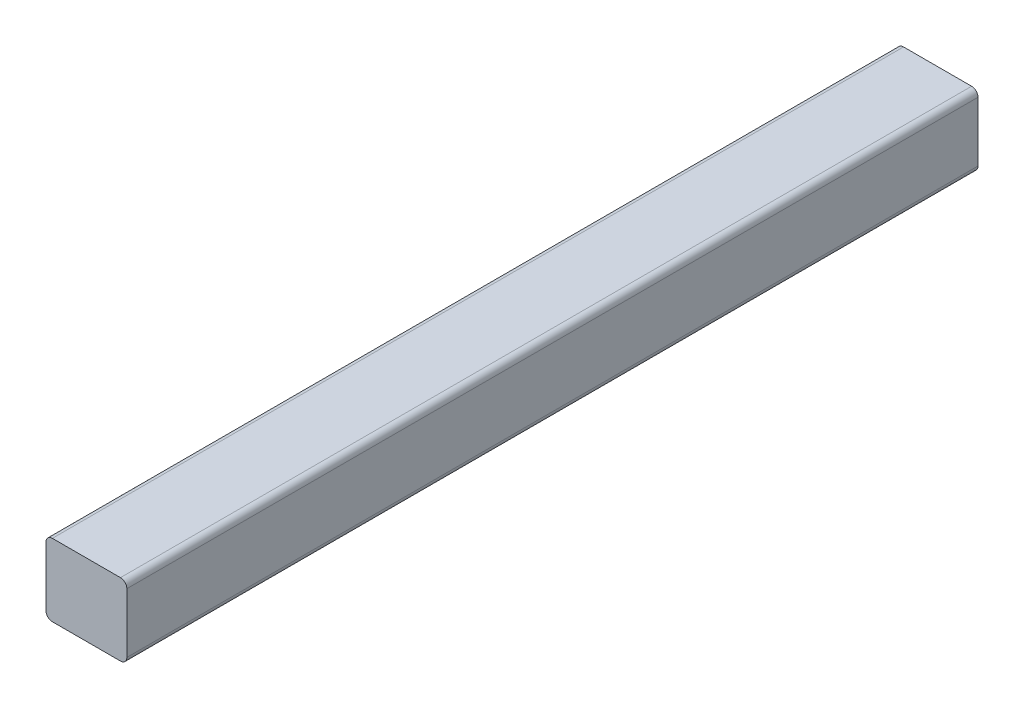
SolidWorks part; units mm, degrees
ref_plane "Ön Düzlem" through (0, 0, 0) normal (0, 0, 1) x (1, 0, 0)
ref_plane "Üst Düzlem" through (0, 0, 0) normal (0, 1, 0) x (1, 0, 0)
ref_plane "Sağ Düzlem" through (0, 0, 0) normal (1, 0, 0) x (0, 0, -1)
sketch "Model" plane through (0, 0, 0) normal (0, 0, 1) x (1, 0, 0)
  line L0 (-9.5, 79.7049) -> (9.5, 79.7049)
  line L1 (60.5945, 121.4987) -> (60.8885, 121.3363)
  line L2 (60.8885, 121.3363) -> (61.139, 121.1124)
  line L3 (61.139, 121.1124) -> (61.3334, 120.8385)
  line L4 (61.3334, 120.8385) -> (61.4619, 120.5282)
  line L5 (61.4619, 120.5282) -> (61.5182, 120.197)
  line L6 (61.5182, 120.197) -> (61.4993, 119.8617)
  line L7 (61.4993, 119.8617) -> (61.4063, 119.5389)
  line L8 (61.4063, 119.5389) -> (45.7726, 92.4605)
  line L9 (45.7726, 92.4605) -> (42.0525, 92.3778)
  line L10 (42.0525, 92.3778) -> (41.4785, 90.992)
  line L11 (58.0621, 81.4174) -> (58.9753, 82.6074)
  line L12 (58.9753, 82.6074) -> (57.1868, 85.8705)
  line L13 (57.1868, 85.8705) -> (72.8206, 112.9489)
  line L14 (72.8206, 112.9489) -> (73.0536, 113.1908)
  line L15 (73.0536, 113.1908) -> (73.3346, 113.3748)
  line L16 (73.3346, 113.3748) -> (73.6495, 113.4917)
  line L17 (73.6495, 113.4917) -> (73.9825, 113.5355)
  line L18 (73.9825, 113.5355) -> (74.317, 113.5041)
  line L19 (74.317, 113.5041) -> (74.636, 113.3991)
  line L20 (74.636, 113.3991) -> (74.9237, 113.2258)
  line L21 (74.9237, 113.2258) -> (89.976, 101.6758)
  line L22 (89.976, 101.6758) -> (90.2179, 101.4427)
  line L23 (90.2179, 101.4427) -> (90.4019, 101.1617)
  line L24 (90.4019, 101.1617) -> (90.5188, 100.8468)
  line L25 (90.5188, 100.8468) -> (90.5626, 100.5138)
  line L26 (90.5626, 100.5138) -> (90.5313, 100.1793)
  line L27 (90.5313, 100.1793) -> (90.4263, 99.8603)
  line L28 (90.4263, 99.8603) -> (90.2529, 99.5726)
  line L29 (90.2529, 99.5726) -> (68.1435, 77.4631)
  line L30 (68.1435, 77.4631) -> (64.5287, 78.3461)
  line L31 (64.5287, 78.3461) -> (63.6156, 77.1561)
  line L32 (77.1561, 63.6156) -> (78.3461, 64.5287)
  line L33 (78.3461, 64.5287) -> (77.4631, 68.1435)
  line L34 (77.4631, 68.1435) -> (99.5726, 90.2529)
  line L35 (99.5726, 90.2529) -> (99.8603, 90.4263)
  line L36 (99.8603, 90.4263) -> (100.1793, 90.5313)
  line L37 (100.1793, 90.5313) -> (100.5138, 90.5626)
  line L38 (100.5138, 90.5626) -> (100.8468, 90.5188)
  line L39 (100.8468, 90.5188) -> (101.1617, 90.4019)
  line L40 (101.1617, 90.4019) -> (101.4427, 90.2179)
  line L41 (101.4427, 90.2179) -> (101.6758, 89.976)
  line L42 (101.6758, 89.976) -> (113.2258, 74.9237)
  line L43 (113.2258, 74.9237) -> (113.3991, 74.636)
  line L44 (113.3991, 74.636) -> (113.5041, 74.317)
  line L45 (113.5041, 74.317) -> (113.5355, 73.9825)
  line L46 (113.5355, 73.9825) -> (113.4917, 73.6495)
  line L47 (113.4917, 73.6495) -> (113.3748, 73.3346)
  line L48 (113.3748, 73.3346) -> (113.1908, 73.0536)
  line L49 (113.1908, 73.0536) -> (112.9489, 72.8206)
  line L50 (112.9489, 72.8206) -> (85.8705, 57.1868)
  line L51 (85.8705, 57.1868) -> (82.6074, 58.9753)
  line L52 (82.6074, 58.9753) -> (81.4174, 58.0621)
  line L53 (90.992, 41.4785) -> (92.3778, 42.0525)
  line L54 (92.3778, 42.0525) -> (92.4605, 45.7726)
  line L55 (92.4605, 45.7726) -> (119.5389, 61.4063)
  line L56 (119.5389, 61.4063) -> (119.8617, 61.4993)
  line L57 (119.8617, 61.4993) -> (120.197, 61.5182)
  line L58 (120.197, 61.5182) -> (120.5282, 61.4619)
  line L59 (120.5282, 61.4619) -> (120.8385, 61.3334)
  line L60 (120.8385, 61.3334) -> (121.1124, 61.139)
  line L61 (121.1124, 61.139) -> (121.3363, 60.8885)
  line L62 (121.3363, 60.8885) -> (121.4987, 60.5945)
  line L63 (121.4987, 60.5945) -> (128.7594, 43.0658)
  line L64 (128.7594, 43.0658) -> (128.8524, 42.743)
  line L65 (128.8524, 42.743) -> (128.8712, 42.4076)
  line L66 (128.8712, 42.4076) -> (128.815, 42.0765)
  line L67 (128.815, 42.0765) -> (128.6864, 41.7662)
  line L68 (128.6864, 41.7662) -> (128.492, 41.4922)
  line L69 (128.492, 41.4922) -> (128.2416, 41.2684)
  line L70 (128.2416, 41.2684) -> (127.9476, 41.1059)
  line L71 (127.9476, 41.1059) -> (97.7455, 33.0133)
  line L72 (97.7455, 33.0133) -> (95.0566, 35.5853)
  line L73 (95.0566, 35.5853) -> (93.6707, 35.0113)
  line L74 (98.6269, 16.5147) -> (100.1141, 16.7105)
  line L75 (100.1141, 16.7105) -> (101.1568, 20.2824)
  line L76 (101.1568, 20.2824) -> (131.3588, 28.375)
  line L77 (131.3588, 28.375) -> (131.6947, 28.3813)
  line L78 (131.6947, 28.3813) -> (132.0235, 28.3127)
  line L79 (132.0235, 28.3127) -> (132.3288, 28.1726)
  line L80 (132.3288, 28.1726) -> (132.5953, 27.9682)
  line L81 (132.5953, 27.9682) -> (132.8096, 27.7095)
  line L82 (132.8096, 27.7095) -> (132.9609, 27.4097)
  line L83 (132.9609, 27.4097) -> (133.0418, 27.0836)
  line L84 (133.0418, 27.0836) -> (135.5183, 8.273)
  line L85 (135.5183, 8.273) -> (135.5246, 7.9371)
  line L86 (135.5246, 7.9371) -> (135.4559, 7.6083)
  line L87 (135.4559, 7.6083) -> (135.3159, 7.303)
  line L88 (135.3159, 7.303) -> (135.1114, 7.0365)
  line L89 (135.1114, 7.0365) -> (134.8528, 6.8222)
  line L90 (134.8528, 6.8222) -> (134.5529, 6.6709)
  line L91 (134.5529, 6.6709) -> (134.2269, 6.59)
  line L92 (134.2269, 6.59) -> (102.9594, 6.59)
  line L93 (102.9594, 6.59) -> (101.0278, 9.7704)
  line L94 (101.0278, 9.7704) -> (99.5406, 9.5746)
  line L95 (99.5406, -9.5746) -> (101.0278, -9.7704)
  line L96 (101.0278, -9.7704) -> (102.9594, -6.59)
  line L97 (102.9594, -6.59) -> (134.2269, -6.59)
  line L98 (134.2269, -6.59) -> (134.5529, -6.6709)
  line L99 (134.5529, -6.6709) -> (134.8528, -6.8222)
  line L100 (134.8528, -6.8222) -> (135.1114, -7.0365)
  line L101 (135.1114, -7.0365) -> (135.3159, -7.303)
  line L102 (135.3159, -7.303) -> (135.4559, -7.6083)
  line L103 (135.4559, -7.6083) -> (135.5246, -7.9371)
  line L104 (135.5246, -7.9371) -> (135.5183, -8.273)
  line L105 (135.5183, -8.273) -> (133.0418, -27.0836)
  line L106 (133.0418, -27.0836) -> (132.9609, -27.4097)
  line L107 (132.9609, -27.4097) -> (132.8096, -27.7095)
  line L108 (132.8096, -27.7095) -> (132.5953, -27.9682)
  line L109 (132.5953, -27.9682) -> (132.3288, -28.1726)
  line L110 (132.3288, -28.1726) -> (132.0235, -28.3127)
  line L111 (132.0235, -28.3127) -> (131.6947, -28.3813)
  line L112 (131.6947, -28.3813) -> (131.3588, -28.375)
  line L113 (131.3588, -28.375) -> (101.1568, -20.2824)
  line L114 (101.1568, -20.2824) -> (100.1141, -16.7105)
  line L115 (100.1141, -16.7105) -> (98.6269, -16.5147)
  line L116 (93.6707, -35.0113) -> (95.0566, -35.5853)
  line L117 (95.0566, -35.5853) -> (97.7455, -33.0133)
  line L118 (97.7455, -33.0133) -> (127.9476, -41.1059)
  line L119 (127.9476, -41.1059) -> (128.2416, -41.2684)
  line L120 (128.2416, -41.2684) -> (128.492, -41.4922)
  line L121 (128.492, -41.4922) -> (128.6864, -41.7662)
  line L122 (128.6864, -41.7662) -> (128.815, -42.0765)
  line L123 (128.815, -42.0765) -> (128.8712, -42.4076)
  line L124 (128.8712, -42.4076) -> (128.8524, -42.743)
  line L125 (128.8524, -42.743) -> (128.7594, -43.0658)
  line L126 (128.7594, -43.0658) -> (121.4987, -60.5945)
  line L127 (121.4987, -60.5945) -> (121.3363, -60.8885)
  line L128 (121.3363, -60.8885) -> (121.1124, -61.139)
  line L129 (121.1124, -61.139) -> (120.8385, -61.3334)
  line L130 (120.8385, -61.3334) -> (120.5282, -61.4619)
  line L131 (120.5282, -61.4619) -> (120.197, -61.5182)
  line L132 (120.197, -61.5182) -> (119.8617, -61.4993)
  line L133 (119.8617, -61.4993) -> (119.5389, -61.4063)
  line L134 (119.5389, -61.4063) -> (92.4605, -45.7726)
  line L135 (92.4605, -45.7726) -> (92.3778, -42.0525)
  line L136 (92.3778, -42.0525) -> (90.992, -41.4785)
  line L137 (81.4174, -58.0621) -> (82.6074, -58.9753)
  line L138 (82.6074, -58.9753) -> (85.8705, -57.1868)
  line L139 (85.8705, -57.1868) -> (112.9489, -72.8206)
  line L140 (112.9489, -72.8206) -> (113.1908, -73.0536)
  line L141 (113.1908, -73.0536) -> (113.3748, -73.3346)
  line L142 (113.3748, -73.3346) -> (113.4917, -73.6495)
  line L143 (113.4917, -73.6495) -> (113.5355, -73.9825)
  line L144 (113.5355, -73.9825) -> (113.5041, -74.317)
  line L145 (113.5041, -74.317) -> (113.3991, -74.636)
  line L146 (113.3991, -74.636) -> (113.2258, -74.9237)
  line L147 (113.2258, -74.9237) -> (101.6758, -89.976)
  line L148 (101.6758, -89.976) -> (101.4427, -90.2179)
  line L149 (101.4427, -90.2179) -> (101.1617, -90.4019)
  line L150 (101.1617, -90.4019) -> (100.8468, -90.5188)
  line L151 (100.8468, -90.5188) -> (100.5138, -90.5626)
  line L152 (100.5138, -90.5626) -> (100.1793, -90.5313)
  line L153 (100.1793, -90.5313) -> (99.8603, -90.4263)
  line L154 (99.8603, -90.4263) -> (99.5726, -90.2529)
  line L155 (99.5726, -90.2529) -> (77.4631, -68.1435)
  line L156 (77.4631, -68.1435) -> (78.3461, -64.5287)
  line L157 (78.3461, -64.5287) -> (77.1561, -63.6156)
  line L158 (63.6156, -77.1561) -> (64.5287, -78.3461)
  line L159 (64.5287, -78.3461) -> (68.1435, -77.4631)
  line L160 (68.1435, -77.4631) -> (90.2529, -99.5726)
  line L161 (90.2529, -99.5726) -> (90.4263, -99.8603)
  line L162 (90.4263, -99.8603) -> (90.5313, -100.1793)
  line L163 (90.5313, -100.1793) -> (90.5626, -100.5138)
  line L164 (90.5626, -100.5138) -> (90.5188, -100.8468)
  line L165 (90.5188, -100.8468) -> (90.4019, -101.1617)
  line L166 (90.4019, -101.1617) -> (90.2179, -101.4427)
  line L167 (90.2179, -101.4427) -> (89.976, -101.6758)
  line L168 (89.976, -101.6758) -> (74.9237, -113.2258)
  line L169 (74.9237, -113.2258) -> (74.636, -113.3991)
  line L170 (74.636, -113.3991) -> (74.317, -113.5041)
  line L171 (74.317, -113.5041) -> (73.9825, -113.5355)
  line L172 (73.9825, -113.5355) -> (73.6495, -113.4917)
  line L173 (73.6495, -113.4917) -> (73.3346, -113.3748)
  line L174 (73.3346, -113.3748) -> (73.0536, -113.1908)
  line L175 (73.0536, -113.1908) -> (72.8206, -112.9489)
  line L176 (72.8206, -112.9489) -> (57.1868, -85.8705)
  line L177 (57.1868, -85.8705) -> (58.9753, -82.6074)
  line L178 (58.9753, -82.6074) -> (58.0621, -81.4174)
  line L179 (41.4785, -90.992) -> (42.0525, -92.3778)
  line L180 (42.0525, -92.3778) -> (45.7726, -92.4605)
  line L181 (45.7726, -92.4605) -> (61.4063, -119.5389)
  line L182 (61.4063, -119.5389) -> (61.4993, -119.8617)
  line L183 (61.4993, -119.8617) -> (61.5182, -120.197)
  line L184 (61.5182, -120.197) -> (61.4619, -120.5282)
  line L185 (61.4619, -120.5282) -> (61.3334, -120.8385)
  line L186 (61.3334, -120.8385) -> (61.139, -121.1124)
  line L187 (61.139, -121.1124) -> (60.8885, -121.3363)
  line L188 (60.8885, -121.3363) -> (60.5945, -121.4987)
  line L189 (60.5945, -121.4987) -> (43.0658, -128.7594)
  line L190 (43.0658, -128.7594) -> (42.743, -128.8524)
  line L191 (42.743, -128.8524) -> (42.4076, -128.8712)
  line L192 (42.4076, -128.8712) -> (42.0765, -128.815)
  line L193 (42.0765, -128.815) -> (41.7662, -128.6864)
  line L194 (41.7662, -128.6864) -> (41.4922, -128.492)
  line L195 (41.4922, -128.492) -> (41.2684, -128.2416)
  line L196 (41.2684, -128.2416) -> (41.1059, -127.9476)
  line L197 (41.1059, -127.9476) -> (33.0133, -97.7455)
  line L198 (33.0133, -97.7455) -> (35.5853, -95.0566)
  line L199 (35.5853, -95.0566) -> (35.0113, -93.6707)
  line L200 (16.5147, -98.6269) -> (16.7105, -100.1141)
  line L201 (16.7105, -100.1141) -> (20.2824, -101.1568)
  line L202 (20.2824, -101.1568) -> (28.375, -131.3588)
  line L203 (28.375, -131.3588) -> (28.3813, -131.6947)
  line L204 (28.3813, -131.6947) -> (28.3127, -132.0235)
  line L205 (28.3127, -132.0235) -> (28.1726, -132.3288)
  line L206 (28.1726, -132.3288) -> (27.9682, -132.5953)
  line L207 (27.9682, -132.5953) -> (27.7095, -132.8096)
  line L208 (27.7095, -132.8096) -> (27.4097, -132.9609)
  line L209 (27.4097, -132.9609) -> (27.0836, -133.0418)
  line L210 (27.0836, -133.0418) -> (8.273, -135.5183)
  line L211 (8.273, -135.5183) -> (7.9371, -135.5246)
  line L212 (7.9371, -135.5246) -> (7.6083, -135.4559)
  line L213 (7.6083, -135.4559) -> (7.303, -135.3159)
  line L214 (7.303, -135.3159) -> (7.0365, -135.1114)
  line L215 (7.0365, -135.1114) -> (6.8222, -134.8528)
  line L216 (6.8222, -134.8528) -> (6.6709, -134.5529)
  line L217 (6.6709, -134.5529) -> (6.59, -134.2269)
  line L218 (6.59, -134.2269) -> (6.59, -102.9594)
  line L219 (6.59, -102.9594) -> (9.7704, -101.0278)
  line L220 (9.7704, -101.0278) -> (9.5746, -99.5406)
  line L221 (-9.5746, -99.5406) -> (-9.7704, -101.0278)
  line L222 (-9.7704, -101.0278) -> (-6.59, -102.9594)
  line L223 (-6.59, -102.9594) -> (-6.59, -134.2269)
  line L224 (-6.59, -134.2269) -> (-6.6709, -134.5529)
  line L225 (-6.6709, -134.5529) -> (-6.8222, -134.8528)
  line L226 (-6.8222, -134.8528) -> (-7.0365, -135.1114)
  line L227 (-7.0365, -135.1114) -> (-7.303, -135.3159)
  line L228 (-7.303, -135.3159) -> (-7.6083, -135.4559)
  line L229 (-7.6083, -135.4559) -> (-7.9371, -135.5246)
  line L230 (-7.9371, -135.5246) -> (-8.273, -135.5183)
  line L231 (-8.273, -135.5183) -> (-27.0836, -133.0418)
  line L232 (-27.0836, -133.0418) -> (-27.4097, -132.9609)
  line L233 (-27.4097, -132.9609) -> (-27.7095, -132.8096)
  line L234 (-27.7095, -132.8096) -> (-27.9682, -132.5953)
  line L235 (-27.9682, -132.5953) -> (-28.1726, -132.3288)
  line L236 (-28.1726, -132.3288) -> (-28.3127, -132.0235)
  line L237 (-28.3127, -132.0235) -> (-28.3813, -131.6947)
  line L238 (-28.3813, -131.6947) -> (-28.375, -131.3588)
  line L239 (-28.375, -131.3588) -> (-20.2824, -101.1568)
  line L240 (-20.2824, -101.1568) -> (-16.7105, -100.1141)
  line L241 (-16.7105, -100.1141) -> (-16.5147, -98.6269)
  line L242 (-35.0113, -93.6707) -> (-35.5853, -95.0566)
  line L243 (-35.5853, -95.0566) -> (-33.0133, -97.7455)
  line L244 (-33.0133, -97.7455) -> (-41.1059, -127.9476)
  line L245 (-41.1059, -127.9476) -> (-41.2684, -128.2416)
  line L246 (-41.2684, -128.2416) -> (-41.4922, -128.492)
  line L247 (-41.4922, -128.492) -> (-41.7662, -128.6864)
  line L248 (-41.7662, -128.6864) -> (-42.0765, -128.815)
  line L249 (-42.0765, -128.815) -> (-42.4076, -128.8712)
  line L250 (-42.4076, -128.8712) -> (-42.743, -128.8524)
  line L251 (-42.743, -128.8524) -> (-43.0658, -128.7594)
  line L252 (-43.0658, -128.7594) -> (-60.5945, -121.4987)
  line L253 (-60.5945, -121.4987) -> (-60.8885, -121.3363)
  line L254 (-60.8885, -121.3363) -> (-61.139, -121.1124)
  line L255 (-61.139, -121.1124) -> (-61.3334, -120.8385)
  line L256 (-61.3334, -120.8385) -> (-61.4619, -120.5282)
  line L257 (-61.4619, -120.5282) -> (-61.5182, -120.197)
  line L258 (-61.5182, -120.197) -> (-61.4993, -119.8617)
  line L259 (-61.4993, -119.8617) -> (-61.4063, -119.5389)
  line L260 (-61.4063, -119.5389) -> (-45.7726, -92.4605)
  line L261 (-45.7726, -92.4605) -> (-42.0525, -92.3778)
  line L262 (-42.0525, -92.3778) -> (-41.4785, -90.992)
  line L263 (-58.0621, -81.4174) -> (-58.9753, -82.6074)
  line L264 (-58.9753, -82.6074) -> (-57.1868, -85.8705)
  line L265 (-57.1868, -85.8705) -> (-72.8206, -112.9489)
  line L266 (-72.8206, -112.9489) -> (-73.0536, -113.1908)
  line L267 (-73.0536, -113.1908) -> (-73.3346, -113.3748)
  line L268 (-73.3346, -113.3748) -> (-73.6495, -113.4917)
  line L269 (-73.6495, -113.4917) -> (-73.9825, -113.5355)
  line L270 (-73.9825, -113.5355) -> (-74.317, -113.5041)
  line L271 (-74.317, -113.5041) -> (-74.636, -113.3991)
  line L272 (-74.636, -113.3991) -> (-74.9237, -113.2258)
  line L273 (-74.9237, -113.2258) -> (-89.976, -101.6758)
  line L274 (-89.976, -101.6758) -> (-90.2179, -101.4427)
  line L275 (-90.2179, -101.4427) -> (-90.4019, -101.1617)
  line L276 (-90.4019, -101.1617) -> (-90.5188, -100.8468)
  line L277 (-90.5188, -100.8468) -> (-90.5626, -100.5138)
  line L278 (-90.5626, -100.5138) -> (-90.5313, -100.1793)
  line L279 (-90.5313, -100.1793) -> (-90.4263, -99.8603)
  line L280 (-90.4263, -99.8603) -> (-90.2529, -99.5726)
  line L281 (-90.2529, -99.5726) -> (-68.1435, -77.4631)
  line L282 (-68.1435, -77.4631) -> (-64.5287, -78.3461)
  line L283 (-64.5287, -78.3461) -> (-63.6156, -77.1561)
  line L284 (-77.1561, -63.6156) -> (-78.3461, -64.5287)
  line L285 (-78.3461, -64.5287) -> (-77.4631, -68.1435)
  line L286 (-77.4631, -68.1435) -> (-99.5726, -90.2529)
  line L287 (-99.5726, -90.2529) -> (-99.8603, -90.4263)
  line L288 (-99.8603, -90.4263) -> (-100.1793, -90.5313)
  line L289 (-100.1793, -90.5313) -> (-100.5138, -90.5626)
  line L290 (-100.5138, -90.5626) -> (-100.8468, -90.5188)
  line L291 (-100.8468, -90.5188) -> (-101.1617, -90.4019)
  line L292 (-101.1617, -90.4019) -> (-101.4427, -90.2179)
  line L293 (-101.4427, -90.2179) -> (-101.6758, -89.976)
  line L294 (-101.6758, -89.976) -> (-113.2258, -74.9237)
  line L295 (-113.2258, -74.9237) -> (-113.3991, -74.636)
  line L296 (-113.3991, -74.636) -> (-113.5041, -74.317)
  line L297 (-113.5041, -74.317) -> (-113.5355, -73.9825)
  line L298 (-113.5355, -73.9825) -> (-113.4917, -73.6495)
  line L299 (-113.4917, -73.6495) -> (-113.3748, -73.3346)
  line L300 (-113.3748, -73.3346) -> (-113.1908, -73.0536)
  line L301 (-113.1908, -73.0536) -> (-112.9489, -72.8206)
  line L302 (-112.9489, -72.8206) -> (-85.8705, -57.1868)
  line L303 (-85.8705, -57.1868) -> (-82.6074, -58.9753)
  line L304 (-82.6074, -58.9753) -> (-81.4174, -58.0621)
  line L305 (-90.992, -41.4785) -> (-92.3778, -42.0525)
  line L306 (-92.3778, -42.0525) -> (-92.4605, -45.7726)
  line L307 (-92.4605, -45.7726) -> (-119.5389, -61.4063)
  line L308 (-119.5389, -61.4063) -> (-119.8617, -61.4993)
  line L309 (-119.8617, -61.4993) -> (-120.197, -61.5182)
  line L310 (-120.197, -61.5182) -> (-120.5282, -61.4619)
  line L311 (-120.5282, -61.4619) -> (-120.8385, -61.3334)
  line L312 (-120.8385, -61.3334) -> (-121.1124, -61.139)
  line L313 (-121.1124, -61.139) -> (-121.3363, -60.8885)
  line L314 (-121.3363, -60.8885) -> (-121.4987, -60.5945)
  line L315 (-121.4987, -60.5945) -> (-128.7594, -43.0658)
  line L316 (-128.7594, -43.0658) -> (-128.8524, -42.743)
  line L317 (-128.8524, -42.743) -> (-128.8712, -42.4076)
  line L318 (-128.8712, -42.4076) -> (-128.815, -42.0765)
  line L319 (-128.815, -42.0765) -> (-128.6864, -41.7662)
  line L320 (-128.6864, -41.7662) -> (-128.492, -41.4922)
  line L321 (-128.492, -41.4922) -> (-128.2416, -41.2684)
  line L322 (-128.2416, -41.2684) -> (-127.9476, -41.1059)
  line L323 (-127.9476, -41.1059) -> (-97.7455, -33.0133)
  line L324 (-97.7455, -33.0133) -> (-95.0566, -35.5853)
  line L325 (-95.0566, -35.5853) -> (-93.6707, -35.0113)
  line L326 (-98.6269, -16.5147) -> (-100.1141, -16.7105)
  line L327 (-100.1141, -16.7105) -> (-101.1568, -20.2824)
  line L328 (-101.1568, -20.2824) -> (-131.3588, -28.375)
  line L329 (-131.3588, -28.375) -> (-131.6947, -28.3813)
  line L330 (-131.6947, -28.3813) -> (-132.0235, -28.3127)
  line L331 (-132.0235, -28.3127) -> (-132.3288, -28.1726)
  line L332 (-132.3288, -28.1726) -> (-132.5953, -27.9682)
  line L333 (-132.5953, -27.9682) -> (-132.8096, -27.7095)
  line L334 (-132.8096, -27.7095) -> (-132.9609, -27.4097)
  line L335 (-132.9609, -27.4097) -> (-133.0418, -27.0836)
  line L336 (-133.0418, -27.0836) -> (-135.5183, -8.273)
  line L337 (-135.5183, -8.273) -> (-135.5246, -7.9371)
  line L338 (-135.5246, -7.9371) -> (-135.4559, -7.6083)
  line L339 (-135.4559, -7.6083) -> (-135.3159, -7.303)
  line L340 (-135.3159, -7.303) -> (-135.1114, -7.0365)
  line L341 (-135.1114, -7.0365) -> (-134.8528, -6.8222)
  line L342 (-134.8528, -6.8222) -> (-134.5529, -6.6709)
  line L343 (-134.5529, -6.6709) -> (-134.2269, -6.59)
  line L344 (-134.2269, -6.59) -> (-102.9594, -6.59)
  line L345 (-102.9594, -6.59) -> (-101.0278, -9.7704)
  line L346 (-101.0278, -9.7704) -> (-99.5406, -9.5746)
  line L347 (-99.5406, 9.5746) -> (-101.0278, 9.7704)
  line L348 (-101.0278, 9.7704) -> (-102.9594, 6.59)
  line L349 (-102.9594, 6.59) -> (-134.2269, 6.59)
  line L350 (-134.2269, 6.59) -> (-134.5529, 6.6709)
  line L351 (-134.5529, 6.6709) -> (-134.8528, 6.8222)
  line L352 (-134.8528, 6.8222) -> (-135.1114, 7.0365)
  line L353 (-135.1114, 7.0365) -> (-135.3159, 7.303)
  line L354 (-135.3159, 7.303) -> (-135.4559, 7.6083)
  line L355 (-135.4559, 7.6083) -> (-135.5246, 7.9371)
  line L356 (-135.5246, 7.9371) -> (-135.5183, 8.273)
  line L357 (-135.5183, 8.273) -> (-133.0418, 27.0836)
  line L358 (-133.0418, 27.0836) -> (-132.9609, 27.4097)
  line L359 (-132.9609, 27.4097) -> (-132.8096, 27.7095)
  line L360 (-132.8096, 27.7095) -> (-132.5953, 27.9682)
  line L361 (-132.5953, 27.9682) -> (-132.3288, 28.1726)
  line L362 (-132.3288, 28.1726) -> (-132.0235, 28.3127)
  line L363 (-132.0235, 28.3127) -> (-131.6947, 28.3813)
  line L364 (-131.6947, 28.3813) -> (-131.3588, 28.375)
  line L365 (-131.3588, 28.375) -> (-101.1568, 20.2824)
  line L366 (-101.1568, 20.2824) -> (-100.1141, 16.7105)
  line L367 (-100.1141, 16.7105) -> (-98.6269, 16.5147)
  line L368 (-93.6707, 35.0113) -> (-95.0566, 35.5853)
  line L369 (-95.0566, 35.5853) -> (-97.7455, 33.0133)
  line L370 (-97.7455, 33.0133) -> (-127.9476, 41.1059)
  line L371 (-127.9476, 41.1059) -> (-128.2416, 41.2684)
  line L372 (-128.2416, 41.2684) -> (-128.492, 41.4922)
  line L373 (-128.492, 41.4922) -> (-128.6864, 41.7662)
  line L374 (-128.6864, 41.7662) -> (-128.815, 42.0765)
  line L375 (-128.815, 42.0765) -> (-128.8712, 42.4076)
  line L376 (-128.8712, 42.4076) -> (-128.8524, 42.743)
  line L377 (-128.8524, 42.743) -> (-128.7594, 43.0658)
  line L378 (-128.7594, 43.0658) -> (-121.4987, 60.5945)
  line L379 (-121.4987, 60.5945) -> (-121.3363, 60.8885)
  line L380 (-121.3363, 60.8885) -> (-121.1124, 61.139)
  line L381 (-121.1124, 61.139) -> (-120.8385, 61.3334)
  line L382 (-120.8385, 61.3334) -> (-120.5282, 61.4619)
  line L383 (-120.5282, 61.4619) -> (-120.197, 61.5182)
  line L384 (-120.197, 61.5182) -> (-119.8617, 61.4993)
  line L385 (-119.8617, 61.4993) -> (-119.5389, 61.4063)
  line L386 (-119.5389, 61.4063) -> (-92.4605, 45.7726)
  line L387 (-92.4605, 45.7726) -> (-92.3778, 42.0525)
  line L388 (-92.3778, 42.0525) -> (-90.992, 41.4785)
  line L389 (-81.4174, 58.0621) -> (-82.6074, 58.9753)
  line L390 (-82.6074, 58.9753) -> (-85.8705, 57.1868)
  line L391 (-85.8705, 57.1868) -> (-112.9489, 72.8206)
  line L392 (-112.9489, 72.8206) -> (-113.1908, 73.0536)
  line L393 (-113.1908, 73.0536) -> (-113.3748, 73.3346)
  line L394 (-113.3748, 73.3346) -> (-113.4917, 73.6495)
  line L395 (-113.4917, 73.6495) -> (-113.5355, 73.9825)
  line L396 (-113.5355, 73.9825) -> (-113.5041, 74.317)
  line L397 (-113.5041, 74.317) -> (-113.3991, 74.636)
  line L398 (-113.3991, 74.636) -> (-113.2258, 74.9237)
  line L399 (-113.2258, 74.9237) -> (-101.6758, 89.976)
  line L400 (-101.6758, 89.976) -> (-101.4427, 90.2179)
  line L401 (-101.4427, 90.2179) -> (-101.1617, 90.4019)
  line L402 (-101.1617, 90.4019) -> (-100.8468, 90.5188)
  line L403 (-100.8468, 90.5188) -> (-100.5138, 90.5626)
  line L404 (-100.5138, 90.5626) -> (-100.1793, 90.5313)
  line L405 (-100.1793, 90.5313) -> (-99.8603, 90.4263)
  line L406 (-99.8603, 90.4263) -> (-99.5726, 90.2529)
  line L407 (-99.5726, 90.2529) -> (-77.4631, 68.1435)
  line L408 (-77.4631, 68.1435) -> (-78.3461, 64.5287)
  line L409 (-78.3461, 64.5287) -> (-77.1561, 63.6156)
  line L410 (-63.6156, 77.1561) -> (-64.5287, 78.3461)
  line L411 (-64.5287, 78.3461) -> (-68.1435, 77.4631)
  line L412 (-68.1435, 77.4631) -> (-90.2529, 99.5726)
  line L413 (-90.2529, 99.5726) -> (-90.4263, 99.8603)
  line L414 (-90.4263, 99.8603) -> (-90.5313, 100.1793)
  line L415 (-90.5313, 100.1793) -> (-90.5626, 100.5138)
  line L416 (-90.5626, 100.5138) -> (-90.5188, 100.8468)
  line L417 (-90.5188, 100.8468) -> (-90.4019, 101.1617)
  line L418 (-90.4019, 101.1617) -> (-90.2179, 101.4427)
  line L419 (-90.2179, 101.4427) -> (-89.976, 101.6758)
  line L420 (-89.976, 101.6758) -> (-74.9237, 113.2258)
  line L421 (-74.9237, 113.2258) -> (-74.636, 113.3991)
  line L422 (-74.636, 113.3991) -> (-74.317, 113.5041)
  line L423 (-74.317, 113.5041) -> (-73.9825, 113.5355)
  line L424 (-73.9825, 113.5355) -> (-73.6495, 113.4917)
  line L425 (-73.6495, 113.4917) -> (-73.3346, 113.3748)
  line L426 (-73.3346, 113.3748) -> (-73.0536, 113.1908)
  line L427 (-73.0536, 113.1908) -> (-72.8206, 112.9489)
  line L428 (-72.8206, 112.9489) -> (-57.1868, 85.8705)
  line L429 (-57.1868, 85.8705) -> (-58.9753, 82.6074)
  line L430 (-58.9753, 82.6074) -> (-58.0621, 81.4174)
  line L431 (-41.4785, 90.992) -> (-42.0525, 92.3778)
  line L432 (-42.0525, 92.3778) -> (-45.7726, 92.4605)
  line L433 (-45.7726, 92.4605) -> (-61.4063, 119.5389)
  line L434 (-61.4063, 119.5389) -> (-61.4993, 119.8617)
  line L435 (-61.4993, 119.8617) -> (-61.5182, 120.197)
  line L436 (-61.5182, 120.197) -> (-61.4619, 120.5282)
  line L437 (-61.4619, 120.5282) -> (-61.3334, 120.8385)
  line L438 (-61.3334, 120.8385) -> (-61.139, 121.1124)
  line L439 (-61.139, 121.1124) -> (-60.8885, 121.3363)
  line L440 (-60.8885, 121.3363) -> (-60.5945, 121.4987)
  line L441 (-60.5945, 121.4987) -> (-43.0658, 128.7594)
  line L442 (-43.0658, 128.7594) -> (-42.743, 128.8524)
  line L443 (-42.743, 128.8524) -> (-42.4076, 128.8712)
  line L444 (-42.4076, 128.8712) -> (-42.0765, 128.815)
  line L445 (-42.0765, 128.815) -> (-41.7662, 128.6864)
  line L446 (-41.7662, 128.6864) -> (-41.4922, 128.492)
  line L447 (-41.4922, 128.492) -> (-41.2684, 128.2416)
  line L448 (-41.2684, 128.2416) -> (-41.1059, 127.9476)
  line L449 (-41.1059, 127.9476) -> (-33.0133, 97.7455)
  line L450 (-33.0133, 97.7455) -> (-35.5853, 95.0566)
  line L451 (-35.5853, 95.0566) -> (-35.0113, 93.6707)
  line L452 (-16.5147, 98.6269) -> (-16.7105, 100.1141)
  line L453 (-16.7105, 100.1141) -> (-20.2824, 101.1568)
  line L454 (-20.2824, 101.1568) -> (-28.375, 131.3588)
  line L455 (-28.375, 131.3588) -> (-28.3813, 131.6947)
  line L456 (-28.3813, 131.6947) -> (-28.3127, 132.0235)
  line L457 (-28.3127, 132.0235) -> (-28.1726, 132.3288)
  line L458 (-28.1726, 132.3288) -> (-27.9682, 132.5953)
  line L459 (-27.9682, 132.5953) -> (-27.7095, 132.8096)
  line L460 (-27.7095, 132.8096) -> (-27.4097, 132.9609)
  line L461 (-27.4097, 132.9609) -> (-27.0836, 133.0418)
  line L462 (-27.0836, 133.0418) -> (-8.273, 135.5183)
  line L463 (-8.273, 135.5183) -> (-7.9371, 135.5246)
  line L464 (-7.9371, 135.5246) -> (-7.6083, 135.4559)
  line L465 (-7.6083, 135.4559) -> (-7.303, 135.3159)
  line L466 (-7.303, 135.3159) -> (-7.0365, 135.1114)
  line L467 (-7.0365, 135.1114) -> (-6.8222, 134.8528)
  line L468 (-6.8222, 134.8528) -> (-6.6709, 134.5529)
  line L469 (-6.6709, 134.5529) -> (-6.59, 134.2269)
  line L470 (-6.59, 134.2269) -> (-6.59, 102.9594)
  line L471 (-6.59, 102.9594) -> (-9.7704, 101.0278)
  line L472 (-9.7704, 101.0278) -> (-9.5746, 99.5406)
  line L473 (9.5746, 99.5406) -> (9.7704, 101.0278)
  line L474 (9.7704, 101.0278) -> (6.59, 102.9594)
  line L475 (6.59, 102.9594) -> (6.59, 134.2269)
  line L476 (6.59, 134.2269) -> (6.6709, 134.5529)
  line L477 (6.6709, 134.5529) -> (6.8222, 134.8528)
  line L478 (6.8222, 134.8528) -> (7.0365, 135.1114)
  line L479 (7.0365, 135.1114) -> (7.303, 135.3159)
  line L480 (7.303, 135.3159) -> (7.6083, 135.4559)
  line L481 (7.6083, 135.4559) -> (7.9371, 135.5246)
  line L482 (7.9371, 135.5246) -> (8.273, 135.5183)
  line L483 (8.273, 135.5183) -> (27.0836, 133.0418)
  line L484 (27.0836, 133.0418) -> (27.4097, 132.9609)
  line L485 (27.4097, 132.9609) -> (27.7095, 132.8096)
  line L486 (27.7095, 132.8096) -> (27.9682, 132.5953)
  line L487 (27.9682, 132.5953) -> (28.1726, 132.3288)
  line L488 (28.1726, 132.3288) -> (28.3127, 132.0235)
  line L489 (28.3127, 132.0235) -> (28.3813, 131.6947)
  line L490 (28.3813, 131.6947) -> (28.375, 131.3588)
  line L491 (28.375, 131.3588) -> (20.2824, 101.1568)
  line L492 (20.2824, 101.1568) -> (16.7105, 100.1141)
  line L493 (16.7105, 100.1141) -> (16.5147, 98.6269)
  line L494 (35.0113, 93.6707) -> (35.5853, 95.0566)
  line L495 (35.5853, 95.0566) -> (33.0133, 97.7455)
  line L496 (33.0133, 97.7455) -> (41.1059, 127.9476)
  line L497 (41.1059, 127.9476) -> (41.2684, 128.2416)
  line L498 (41.2684, 128.2416) -> (41.4922, 128.492)
  line L499 (41.4922, 128.492) -> (41.7662, 128.6864)
  line L500 (41.7662, 128.6864) -> (42.0765, 128.815)
  line L501 (42.0765, 128.815) -> (42.4076, 128.8712)
  line L502 (42.4076, 128.8712) -> (42.743, 128.8524)
  line L503 (42.743, 128.8524) -> (43.0658, 128.7594)
  line L504 (43.0658, 128.7594) -> (60.5945, 121.4987)
  line L505 (-9.5, 80.2049) -> (9.5, 80.2049)
  line L506 (10.5, 80.7049) -> (10.5, 83.8451)
  line L507 (10.5, -80.7049) -> (10.5, -83.8451)
  line L508 (27.7776, -94.5021) -> (26.5086, -90.1848)
  line L509 (2.6574, -93.9624) -> (2.7847, -98.4606)
  line L510 (-27.7776, 94.5021) -> (-26.5086, 90.1848)
  line L511 (-2.6574, 93.9624) -> (-2.7847, 98.4606)
  line L512 (94.5021, 27.7776) -> (90.1848, 26.5086)
  line L513 (93.9624, 2.6574) -> (98.4606, 2.7847)
  line L514 (-94.5021, -27.7776) -> (-90.1848, -26.5086)
  line L515 (-93.9624, -2.6574) -> (-98.4606, -2.7847)
  line L516 (55.6209, -81.2931) -> (53.0798, -77.5792)
  line L517 (31.5634, -88.5424) -> (33.0744, -92.7811)
  line L518 (-55.6209, 81.2931) -> (-53.0798, 77.5792)
  line L519 (-31.5634, 88.5424) -> (-33.0744, 92.7811)
  line L520 (81.2931, 55.6209) -> (77.5792, 53.0798)
  line L521 (88.5424, 31.5634) -> (92.7811, 33.0744)
  line L522 (-81.2931, -55.6209) -> (-77.5792, -53.0798)
  line L523 (-88.5424, -31.5634) -> (-92.7811, -33.0744)
  line L524 (78.0195, -60.1265) -> (74.4552, -57.3796)
  line L525 (57.3796, -74.4552) -> (60.1265, -78.0195)
  line L526 (-78.0195, 60.1265) -> (-74.4552, 57.3796)
  line L527 (-57.3796, 74.4552) -> (-60.1265, 78.0195)
  line L528 (60.1265, 78.0195) -> (57.3796, 74.4552)
  line L529 (74.4552, 57.3796) -> (78.0195, 60.1265)
  line L530 (-60.1265, -78.0195) -> (-57.3796, -74.4552)
  line L531 (-74.4552, -57.3796) -> (-78.0195, -60.1265)
  line L532 (92.7811, -33.0744) -> (88.5424, -31.5634)
  line L533 (77.5792, -53.0798) -> (81.2931, -55.6209)
  line L534 (-92.7811, 33.0744) -> (-88.5424, 31.5634)
  line L535 (-77.5792, 53.0798) -> (-81.2931, 55.6209)
  line L536 (33.0744, 92.7811) -> (31.5634, 88.5424)
  line L537 (53.0798, 77.5792) -> (55.6209, 81.2931)
  line L538 (-33.0744, -92.7811) -> (-31.5634, -88.5424)
  line L539 (-53.0798, -77.5792) -> (-55.6209, -81.2931)
  line L540 (98.4606, -2.7847) -> (93.9624, -2.6574)
  line L541 (90.1848, -26.5086) -> (94.5021, -27.7776)
  line L542 (-98.4606, 2.7847) -> (-93.9624, 2.6574)
  line L543 (-90.1848, 26.5086) -> (-94.5021, 27.7776)
  line L544 (2.7847, 98.4606) -> (2.6574, 93.9624)
  line L545 (26.5086, 90.1848) -> (27.7776, 94.5021)
  line L546 (-2.7847, -98.4606) -> (-2.6574, -93.9624)
  line L547 (-26.5086, -90.1848) -> (-27.7776, -94.5021)
  line L548 (9.5, -79.7049) -> (-9.5, -79.7049)
  line L549 (10, 80.7049) -> (10, 84.4097)
  line L550 (-10.5, -80.7049) -> (-10.5, -83.8451)
  line L551 (-10, 80.7049) -> (-10, 84.4097)
  line L552 (9.5, -80.2049) -> (-9.5, -80.2049)
  line L553 (-10, -80.7049) -> (-10, -84.4097)
  line L554 (10, -80.7049) -> (10, -84.4097)
  line L555 (-10.5, 80.7049) -> (-10.5, 83.8451)
  line L556 (-7.7629, 39.0257) -> (-11.9363, 62.6943)
  line L557 (7.7629, 39.0257) -> (11.9363, 62.6943)
  line L558 (16.6584, 36.1354) -> (27.1941, 57.7368)
  line L559 (29.2191, 27.0095) -> (46.5075, 43.7048)
  line L560 (22.4686, 27.2158) -> (18.9406, 29.779)
  line L561 (34.7168, 19.4426) -> (55.9373, 30.7257)
  line L562 (39.5145, 4.6766) -> (63.3144, 8.0215)
  line L563 (34.1745, 8.8113) -> (32.8269, 12.9587)
  line L564 (39.5145, -4.6766) -> (63.3144, -8.0215)
  line L565 (34.7168, -19.4426) -> (55.9373, -30.7257)
  line L566 (32.8269, -12.9587) -> (34.1745, -8.8113)
  line L567 (29.2191, -27.0095) -> (46.5075, -43.7048)
  line L568 (16.6584, -36.1354) -> (27.1941, -57.7368)
  line L569 (18.9406, -29.779) -> (22.4686, -27.2158)
  line L570 (7.7629, -39.0257) -> (11.9363, -62.6943)
  line L571 (-7.7629, -39.0257) -> (-11.9363, -62.6943)
  line L572 (-2.1804, -35.2247) -> (2.1804, -35.2247)
  line L573 (-16.6584, -36.1354) -> (-27.1941, -57.7368)
  line L574 (-29.2191, -27.0095) -> (-46.5075, -43.7048)
  line L575 (-22.4686, -27.2158) -> (-18.9406, -29.779)
  line L576 (-5, -24.4949) -> (-5, -27.9898)
  line L578 (-34.7168, -19.4426) -> (-55.9373, -30.7257)
  line L579 (-39.5145, -4.6766) -> (-63.3144, -8.0215)
  line L580 (2.1804, 35.2247) -> (-2.1804, 35.2247)
  line L581 (-34.1745, -8.8113) -> (-32.8269, -12.9587)
  line L582 (-39.5145, 4.6766) -> (-63.3144, 8.0215)
  line L583 (-34.7168, 19.4426) -> (-55.9373, 30.7257)
  line L584 (-32.8269, 12.9587) -> (-34.1745, 8.8113)
  line L585 (-29.2191, 27.0095) -> (-46.5075, 43.7048)
  line L586 (-16.6584, 36.1354) -> (-27.1941, 57.7368)
  line L587 (-18.9406, 29.779) -> (-22.4686, 27.2158)
  line L588 (0, 20.25) -> (-4, 20.25)
  line L589 (0, 20.25) -> (4, 20.25)
  line L590 (5, -24.4949) -> (5, -27.9898)
  line L591 (0, -28.9898) -> (4, -28.9898)
  line L593 (0, -28.9898) -> (-4, -28.9898)
  line L594 (4.75, 21) -> (4.75, 27.9898)
  line L595 (0, 28.7398) -> (4, 28.7398)
  line L596 (0, 28.7398) -> (-4, 28.7398)
  line L597 (-4.75, 21) -> (-4.75, 27.9898)
  arc A0 (145, 0) -> (64.7137, 129.758) centre (0, 0) ccw
  arc A1 (58.0621, 81.4174) -> (41.4785, 90.992) centre (0, 0) ccw
  arc A2 (77.1561, 63.6156) -> (63.6156, 77.1561) centre (0, 0) ccw
  arc A3 (90.992, 41.4785) -> (81.4174, 58.0621) centre (0, 0) ccw
  arc A4 (98.6269, 16.5147) -> (93.6707, 35.0113) centre (0, 0) ccw
  arc A5 (99.5406, -9.5746) -> (99.5406, 9.5746) centre (0, 0) ccw
  arc A6 (93.6707, -35.0113) -> (98.6269, -16.5147) centre (0, 0) ccw
  arc A7 (81.4174, -58.0621) -> (90.992, -41.4785) centre (0, 0) ccw
  arc A8 (63.6156, -77.1561) -> (77.1561, -63.6156) centre (0, 0) ccw
  arc A9 (41.4785, -90.992) -> (58.0621, -81.4174) centre (0, 0) ccw
  arc A10 (16.5147, -98.6269) -> (35.0113, -93.6707) centre (0, 0) ccw
  arc A11 (-9.5746, -99.5406) -> (9.5746, -99.5406) centre (0, 0) ccw
  arc A12 (-35.0113, -93.6707) -> (-16.5147, -98.6269) centre (0, 0) ccw
  arc A13 (-58.0621, -81.4174) -> (-41.4785, -90.992) centre (0, 0) ccw
  arc A14 (-77.1561, -63.6156) -> (-63.6156, -77.1561) centre (0, 0) ccw
  arc A15 (-90.992, -41.4785) -> (-81.4174, -58.0621) centre (0, 0) ccw
  arc A16 (-98.6269, -16.5147) -> (-93.6707, -35.0113) centre (0, 0) ccw
  arc A17 (-99.5406, 9.5746) -> (-99.5406, -9.5746) centre (0, 0) ccw
  arc A18 (-93.6707, 35.0113) -> (-98.6269, 16.5147) centre (0, 0) ccw
  arc A19 (-81.4174, 58.0621) -> (-90.992, 41.4785) centre (0, 0) ccw
  arc A20 (-63.6156, 77.1561) -> (-77.1561, 63.6156) centre (0, 0) ccw
  arc A21 (-41.4785, 90.992) -> (-58.0621, 81.4174) centre (0, 0) ccw
  arc A22 (-16.5147, 98.6269) -> (-35.0113, 93.6707) centre (0, 0) ccw
  arc A23 (9.5746, 99.5406) -> (-9.5746, 99.5406) centre (0, 0) ccw
  arc A24 (35.0113, 93.6707) -> (16.5147, 98.6269) centre (0, 0) ccw
  arc A25 (64.7137, 129.758) -> (145, 0) centre (0, 0) ccw
  arc A26 (94, 0) -> (-94, 0) centre (0, 0) ccw
  arc A27 (-10, 84.4097) -> (-10, -84.4097) centre (0, 0) ccw
  arc A28 (-94, 0) -> (94, 0) centre (0, 0) ccw
  arc A29 (2.7847, -98.4606) -> (27.7776, -94.5021) centre (0, 0) ccw
  arc A30 (2.6574, -93.9624) -> (26.5086, -90.1848) centre (0, 0) ccw
  arc A31 (-2.7847, 98.4606) -> (-27.7776, 94.5021) centre (0, 0) ccw
  arc A32 (-2.6574, 93.9624) -> (-26.5086, 90.1848) centre (0, 0) ccw
  arc A33 (98.4606, 2.7847) -> (94.5021, 27.7776) centre (0, 0) ccw
  arc A34 (93.9624, 2.6574) -> (90.1848, 26.5086) centre (0, 0) ccw
  arc A35 (-98.4606, -2.7847) -> (-94.5021, -27.7776) centre (0, 0) ccw
  arc A36 (-93.9624, -2.6574) -> (-90.1848, -26.5086) centre (0, 0) ccw
  arc A37 (33.0744, -92.7811) -> (55.6209, -81.2931) centre (0, 0) ccw
  arc A38 (31.5634, -88.5424) -> (53.0798, -77.5792) centre (0, 0) ccw
  arc A39 (-33.0744, 92.7811) -> (-55.6209, 81.2931) centre (0, 0) ccw
  arc A40 (-31.5634, 88.5424) -> (-53.0798, 77.5792) centre (0, 0) ccw
  arc A41 (92.7811, 33.0744) -> (81.2931, 55.6209) centre (0, 0) ccw
  arc A42 (88.5424, 31.5634) -> (77.5792, 53.0798) centre (0, 0) ccw
  arc A43 (-92.7811, -33.0744) -> (-81.2931, -55.6209) centre (0, 0) ccw
  arc A44 (-88.5424, -31.5634) -> (-77.5792, -53.0798) centre (0, 0) ccw
  arc A45 (60.1265, -78.0195) -> (78.0195, -60.1265) centre (0, 0) ccw
  arc A46 (57.3796, -74.4552) -> (74.4552, -57.3796) centre (0, 0) ccw
  arc A47 (-60.1265, 78.0195) -> (-78.0195, 60.1265) centre (0, 0) ccw
  arc A48 (-57.3796, 74.4552) -> (-74.4552, 57.3796) centre (0, 0) ccw
  arc A49 (78.0195, 60.1265) -> (60.1265, 78.0195) centre (0, 0) ccw
  arc A50 (74.4552, 57.3796) -> (57.3796, 74.4552) centre (0, 0) ccw
  arc A51 (-78.0195, -60.1265) -> (-60.1265, -78.0195) centre (0, 0) ccw
  arc A52 (-74.4552, -57.3796) -> (-57.3796, -74.4552) centre (0, 0) ccw
  arc A53 (81.2931, -55.6209) -> (92.7811, -33.0744) centre (0, 0) ccw
  arc A54 (77.5792, -53.0798) -> (88.5424, -31.5634) centre (0, 0) ccw
  arc A55 (-81.2931, 55.6209) -> (-92.7811, 33.0744) centre (0, 0) ccw
  arc A56 (-77.5792, 53.0798) -> (-88.5424, 31.5634) centre (0, 0) ccw
  arc A57 (55.6209, 81.2931) -> (33.0744, 92.7811) centre (0, 0) ccw
  arc A58 (53.0798, 77.5792) -> (31.5634, 88.5424) centre (0, 0) ccw
  arc A59 (-55.6209, -81.2931) -> (-33.0744, -92.7811) centre (0, 0) ccw
  arc A60 (-53.0798, -77.5792) -> (-31.5634, -88.5424) centre (0, 0) ccw
  arc A61 (94.5021, -27.7776) -> (98.4606, -2.7847) centre (0, 0) ccw
  arc A62 (90.1848, -26.5086) -> (93.9624, -2.6574) centre (0, 0) ccw
  arc A63 (-94.5021, 27.7776) -> (-98.4606, 2.7847) centre (0, 0) ccw
  arc A64 (-90.1848, 26.5086) -> (-93.9624, 2.6574) centre (0, 0) ccw
  arc A65 (27.7776, 94.5021) -> (2.7847, 98.4606) centre (0, 0) ccw
  arc A66 (26.5086, 90.1848) -> (2.6574, 93.9624) centre (0, 0) ccw
  arc A67 (-27.7776, -94.5021) -> (-2.7847, -98.4606) centre (0, 0) ccw
  arc A68 (-26.5086, -90.1848) -> (-2.6574, -93.9624) centre (0, 0) ccw
  arc A69 (9.5, 80.2049) -> (10, 80.7049) centre (9.5, 80.7049) ccw
  arc A70 (-10, 80.7049) -> (-9.5, 80.2049) centre (-9.5, 80.7049) ccw
  arc A71 (-9.5, -80.2049) -> (-10, -80.7049) centre (-9.5, -80.7049) ccw
  arc A72 (10, -80.7049) -> (9.5, -80.2049) centre (9.5, -80.7049) ccw
  arc A73 (10, -84.4097) -> (10, 84.4097) centre (0, 0) ccw
  arc A74 (9.5, 79.7049) -> (10.5, 80.7049) centre (9.5, 80.7049) ccw
  arc A75 (10.5, -83.8451) -> (10.5, 83.8451) centre (0, 0) ccw
  arc A76 (10.5, -80.7049) -> (9.5, -79.7049) centre (9.5, -80.7049) ccw
  arc A77 (-9.5, -79.7049) -> (-10.5, -80.7049) centre (-9.5, -80.7049) ccw
  arc A78 (-10.5, 83.8451) -> (-10.5, -83.8451) centre (0, 0) ccw
  arc A79 (-10.5, 80.7049) -> (-9.5, 79.7049) centre (-9.5, 80.7049) ccw
  arc A80 (6.5924, 69.7096) -> (-6.5924, 69.7096) centre (0, 0) ccw
  arc A81 (4, 28.7398) -> (4.75, 27.9898) centre (4, 27.9898) cw
  arc A82 (2.1804, 35.2247) -> (7.7629, 39.0257) centre (2.1804, 41.2247) ccw
  arc A83 (46.3076, 52.5213) -> (35.6409, 60.2711) centre (0, 0) ccw
  arc A84 (22.4686, 27.2158) -> (29.2191, 27.0095) centre (25.9953, 32.0699) ccw
  arc A85 (46.3076, 52.5213) -> (46.5075, 43.7048) centre (42.3396, 48.0208) cw
  arc A86 (27.1941, 57.7368) -> (35.6409, 60.2711) centre (32.5869, 55.1066) cw
  arc A87 (18.9406, 29.779) -> (16.6584, 36.1354) centre (22.4673, 34.6331) cw
  arc A88 (68.3349, 15.2717) -> (64.2606, 27.8112) centre (0, 0) ccw
  arc A89 (34.1745, 8.8113) -> (39.5145, 4.6766) centre (39.8808, 10.6654) ccw
  arc A90 (68.3349, 15.2717) -> (63.3144, 8.0215) centre (62.4794, 13.9631) cw
  arc A91 (55.9373, 30.7257) -> (64.2606, 27.8112) centre (58.7542, 25.4281) cw
  arc A92 (32.8269, 12.9587) -> (34.7168, 19.4426) centre (38.5332, 14.8128) cw
  arc A93 (64.2606, -27.8112) -> (68.3349, -15.2717) centre (0, 0) ccw
  arc A94 (32.8269, -12.9587) -> (34.7168, -19.4426) centre (38.5332, -14.8128) ccw
  arc A95 (64.2606, -27.8112) -> (55.9373, -30.7257) centre (58.7542, -25.4281) cw
  arc A96 (63.3144, -8.0215) -> (68.3349, -15.2717) centre (62.4794, -13.9631) cw
  arc A97 (34.1745, -8.8113) -> (39.5145, -4.6766) centre (39.8808, -10.6654) cw
  arc A98 (6.5924, 69.7096) -> (11.9363, 62.6943) centre (6.0275, 63.7362) cw
  arc A99 (35.6409, -60.2711) -> (46.3076, -52.5213) centre (0, 0) ccw
  arc A100 (18.9406, -29.779) -> (16.6584, -36.1354) centre (22.4673, -34.6331) ccw
  arc A101 (-11.9363, 62.6943) -> (-6.5924, 69.7096) centre (-6.0275, 63.7362) cw
  arc A102 (35.6409, -60.2711) -> (27.1941, -57.7368) centre (32.5869, -55.1066) cw
  arc A103 (46.5075, -43.7048) -> (46.3076, -52.5213) centre (42.3396, -48.0208) cw
  arc A104 (22.4686, -27.2158) -> (29.2191, -27.0095) centre (25.9953, -32.0699) cw
  arc A105 (-6.5924, -69.7096) -> (6.5924, -69.7096) centre (0, 0) ccw
  arc A106 (-2.1804, -35.2247) -> (-7.7629, -39.0257) centre (-2.1804, -41.2247) ccw
  arc A107 (-6.5924, -69.7096) -> (-11.9363, -62.6943) centre (-6.0275, -63.7362) cw
  arc A108 (11.9363, -62.6943) -> (6.5924, -69.7096) centre (6.0275, -63.7362) cw
  arc A109 (2.1804, -35.2247) -> (7.7629, -39.0257) centre (2.1804, -41.2247) cw
  arc A110 (-46.3076, -52.5213) -> (-35.6409, -60.2711) centre (0, 0) ccw
  arc A111 (-22.4686, -27.2158) -> (-29.2191, -27.0095) centre (-25.9953, -32.0699) ccw
  arc A112 (-46.3076, -52.5213) -> (-46.5075, -43.7048) centre (-42.3396, -48.0208) cw
  arc A113 (-27.1941, -57.7368) -> (-35.6409, -60.2711) centre (-32.5869, -55.1066) cw
  arc A114 (-18.9406, -29.779) -> (-16.6584, -36.1354) centre (-22.4673, -34.6331) cw
  arc A115 (-68.3349, -15.2717) -> (-64.2606, -27.8112) centre (0, 0) ccw
  arc A116 (-34.1745, -8.8113) -> (-39.5145, -4.6766) centre (-39.8808, -10.6654) ccw
  arc A117 (-68.3349, -15.2717) -> (-63.3144, -8.0215) centre (-62.4794, -13.9631) cw
  arc A118 (-55.9373, -30.7257) -> (-64.2606, -27.8112) centre (-58.7542, -25.4281) cw
  arc A119 (-32.8269, -12.9587) -> (-34.7168, -19.4426) centre (-38.5332, -14.8128) cw
  arc A120 (-64.2606, 27.8112) -> (-68.3349, 15.2717) centre (0, 0) ccw
  arc A121 (-32.8269, 12.9587) -> (-34.7168, 19.4426) centre (-38.5332, 14.8128) ccw
  arc A122 (-64.2606, 27.8112) -> (-55.9373, 30.7257) centre (-58.7542, 25.4281) cw
  arc A123 (-63.3144, 8.0215) -> (-68.3349, 15.2717) centre (-62.4794, 13.9631) cw
  arc A124 (-34.1745, 8.8113) -> (-39.5145, 4.6766) centre (-39.8808, 10.6654) cw
  arc A125 (-35.6409, 60.2711) -> (-46.3076, 52.5213) centre (0, 0) ccw
  arc A126 (-18.9406, 29.779) -> (-16.6584, 36.1354) centre (-22.4673, 34.6331) ccw
  arc A127 (-35.6409, 60.2711) -> (-27.1941, 57.7368) centre (-32.5869, 55.1066) cw
  arc A128 (-46.5075, 43.7048) -> (-46.3076, 52.5213) centre (-42.3396, 48.0208) cw
  arc A129 (-22.4686, 27.2158) -> (-29.2191, 27.0095) centre (-25.9953, 32.0699) cw
  circle A130 centre (-72.5, 0) radius 3
  circle A131 centre (-58.6537, 42.6144) radius 3
  circle A132 centre (-22.4037, 68.9516) radius 3
  circle A133 centre (22.4037, 68.9516) radius 3
  circle A134 centre (58.6537, 42.6144) radius 3
  circle A135 centre (72.5, 0) radius 3
  circle A136 centre (58.6537, -42.6144) radius 3
  circle A137 centre (22.4037, -68.9516) radius 3
  circle A138 centre (-22.4037, -68.9516) radius 3
  circle A139 centre (-58.6537, -42.6144) radius 3
  arc A140 (5, -27.9898) -> (4, -28.9898) centre (4, -27.9898) cw
  arc A141 (-4, -28.9898) -> (-5, -27.9898) centre (-4, -27.9898) cw
  arc A142 (-2.1804, 35.2247) -> (-7.7629, 39.0257) centre (-2.1804, 41.2247) cw
  arc A143 (-4.75, 21) -> (-4, 20.25) centre (-4, 21) ccw
  arc A144 (4, 20.25) -> (4.75, 21) centre (4, 21) ccw
  arc A145 (-4.75, 27.9898) -> (-4, 28.7398) centre (-4, 27.9898) cw
  arc A146 (-4.75, 24.4427) -> (4.75, 24.4427) centre (0, 0) ccw
  point P656 (9.8496, 50.86)
  point P657 (0, 70.0206)
  point P659 (7.0927, 35.2247)
  point P669 (26.4427, 24.3284)
  point P674 (14.9665, 32.6664)
  point P683 (35.6925, 4.1395)
  point P691 (31.3089, 17.6306)
  point P700 (31.3089, -17.6306)
  point P705 (35.6925, -4.1395)
  point P714 (14.9665, -32.6664)
  point P719 (26.4427, -24.3284)
  point P728 (-7.0927, -35.2247)
  point P733 (7.0927, -35.2247)
  point P742 (-26.4427, -24.3284)
  point P747 (-14.9665, -32.6664)
  point P756 (-35.6925, -4.1395)
  point P761 (-31.3089, -17.6306)
  point P770 (-31.3089, 17.6306)
  point P777 (-7.0927, 35.2247)
  point P779 (-35.6925, 4.1395)
  point P790 (-14.9665, 32.6664)
  point P795 (-26.4427, 24.3284)
  point P812 (0, 0)
  point P831 (0, 0)
  dimension "D3" = 2
  dimension "D2" = 10
  dimension "D4" = 6
  dimension "D1" = 0.5
extrude "Yükseklik-Ekstrüzyon1" add sketch "Model" along normal blind 100 contours A145 L597 A143 L588 L589 A144 L594 A81 L595 L596
